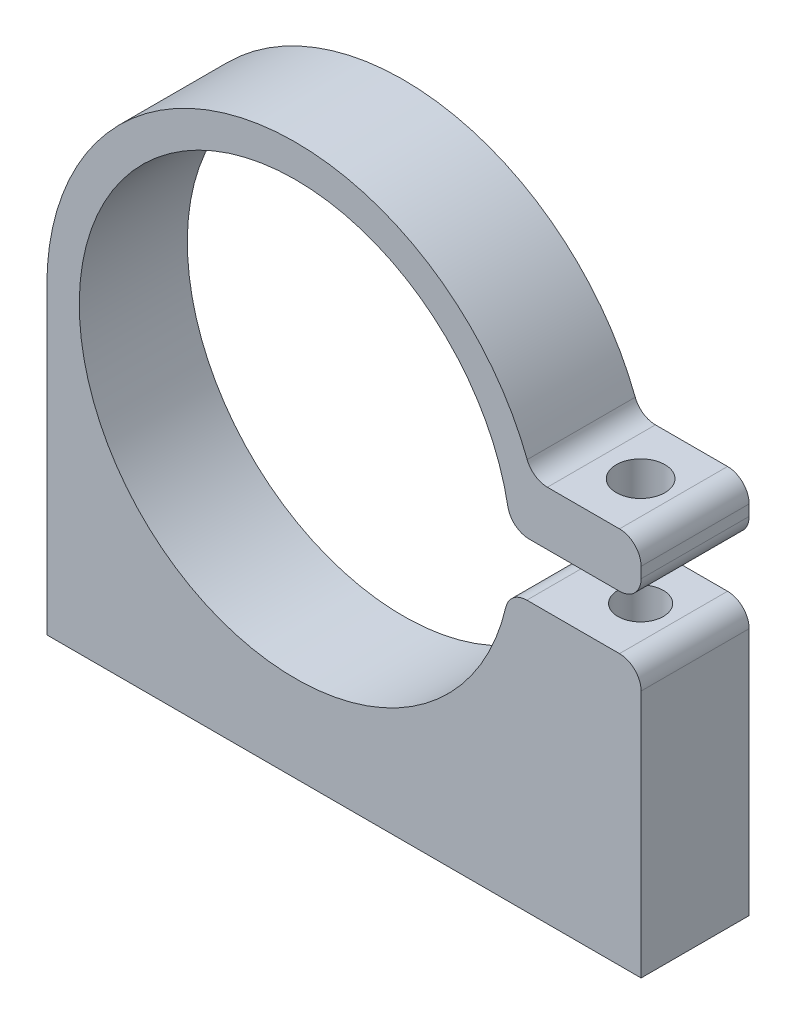
SolidWorks part; units mm, degrees
material "Сплав 2024"
ref_plane "Спереди" through (0, 0, 0) normal (0, 0, 1) x (1, 0, 0)
ref_plane "Сверху" through (0, 0, 0) normal (0, 1, 0) x (1, 0, 0)
ref_plane "Справа" through (0, 0, 0) normal (1, 0, 0) x (0, 0, -1)
sketch "Эскиз1" plane through (0, 0, 0) normal (0, 0, 1) x (1, 0, 0)
  line L0 (32, -3) -> (19.7737, -3)
  line L1 (19.8997, 2) -> (32, 2)
  line L2 (-23, 0) -> (-23, -28)
  line L3 (-23, -28) -> (32, -28)
  line L4 (32, -3) -> (32, -28)
  line L5 (32, 2) -> (32, 7)
  line L6 (32, 7) -> (21.9089, 7)
  arc A0 (19.8997, 2) -> (19.7737, -3) centre (0, 0) ccw
  arc A1 (21.9089, 7) -> (-23, 0) centre (0, 0) ccw
  circle A3 centre (0, 0) radius 23 construction
  circle A4 centre (0, 0) radius 20 construction
  point P4 (20.0824, 6.1398)
  point P12 (24, 0)
  dimension "D1" = 40
  dimension "D3" = 28
  dimension "D4" = 55
  dimension "D5" = 5
  dimension "D6" = 5
  dimension "D7" = 25
  dimension "D2" = 3
extrude "Бобышка-Вытянуть1" add sketch "Эскиз1" along normal blind 10
sketch "Эскиз2" plane through (0, 7, 0) normal (0, 1, 0) x (1, 0, 0)
  line L0 (26.9545, 0) -> (26.9545, -10) construction
  line L1 (32, -10) -> (32, 0) construction
  line L2 (32, -10) -> (21.9089, -10) construction
  line L3 (23.1247, -5) -> (32, -5) construction
fillet "Скругление1" radius 2 6 edges at (32, 2, 5) (32, 7, 5) (32, -3, 5) (19.7737, -3, 5) (19.8997, 2, 5) (21.9089, 7, 5)
hole_wizard "Отверстие с зазором M41" positions "Эскиз4" profile "Эскиз3" hole size "M4" standard "Ansi Metric"
sketch "Эскиз4" plane through (0, 7, 0) normal (0, 1, 0) x (1, 0, 0)
  line L0 (26.9545, 0) -> (26.9545, -10) construction
  point P0 (26.9545, -5)
sketch "Эскиз3" plane through (26.9545, 7, 5) normal (1, 0, 0) x (0, 0, 1)
  line L0 (0, 0) -> (0, 5)
  line L1 (0, 5) -> (2.25, 5)
  line L2 (2.25, 5) -> (2.25, 0)
  line L5 (2.25, 0) -> (0, 0)
  line L11 (0, -6.35) -> (0, 107.95) construction
  dimension "Диаметр сквозного отверстия" = 4.5
  dimension "Глубина сквозного отверстия" = 5
hole_wizard "Отверстие обработанное метчиком M5x0.81" positions "Эскиз6" profile "Эскиз5" tap size "M5x0.8" standard "Ansi Metric" end condition through all
sketch "Эскиз6" plane through (0, -3, 0) normal (0, 1, 0) x (1, 0, 0)
  line L0 (26.9545, 0) -> (26.9545, -10) construction
  point P0 (26.9545, -5)
sketch "Эскиз5" plane through (26.9545, -3, 5) normal (1, 0, 0) x (0, 0, 1)
  line L0 (0, 0) -> (0, 25)
  line L1 (0, 25) -> (2.1, 25)
  line L2 (2.1, 25) -> (2.1, 0)
  line L5 (2.1, 0) -> (0, 0)
  line L11 (0, -6.35) -> (0, 107.95) construction
  dimension "Диаметр проходного сверла" = 4.2
  dimension "Глубина проходного сверла" = 25
cosmetic thread "Отверстие резьбы1" parameters "D2"=5
sketch "Эскиз7" plane through (0, -28, 0) normal (0, -1, 0) x (1, 0, 0)
  line L0 (-23, 5) -> (3.4016, 5) construction
  line L1 (-23, 10) -> (-23, 0) construction
  line L2 (-15, 10) -> (-15, 0) construction
  line L3 (-23, 10) -> (32, 10) construction
  dimension "D1" = 8
hole_wizard "Отверстие обработанное метчиком M5x0.82" positions "Эскиз9" profile "Эскиз8" tap size "M5x0.8" standard "Ansi Metric"
sketch "Эскиз9" plane through (0, -28, 0) normal (0, -1, 0) x (-1, 0, 0)
  line L0 (15, -10) -> (15, 0) construction
  point P0 (15, -5)
sketch "Эскиз8" plane through (-15, -28, 5) normal (1, 0, 0) x (0, 0, -1)
  line L0 (0, 0) -> (0, 11.2618)
  line L1 (0, 11.2618) -> (2.1, 10)
  line L2 (2.1, 10) -> (2.1, 0)
  line L5 (2.1, 0) -> (0, 0)
  line L10 (0, 11.2618) -> (-2.1, 10) construction
  line L11 (0, -6.35) -> (0, 107.95) construction
  dimension "Диаметр сверла" = 4.2
  dimension "Глубина сверла" = 10
  dimension "Угол заточки сверла" = 118
cosmetic thread "Отверстие резьбы2" parameters "D1"=10, "D2"=5
